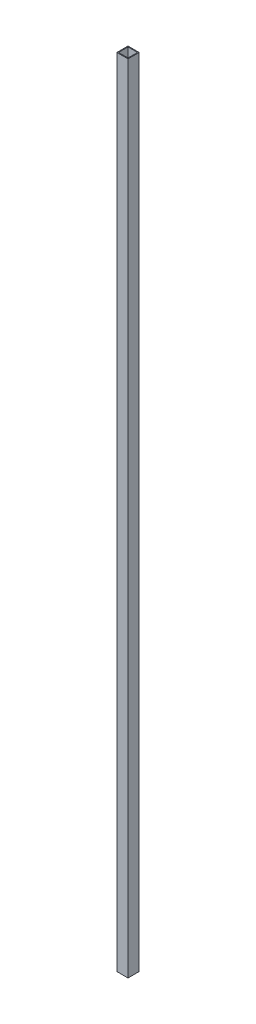
SolidWorks part; units mm, degrees
ref_plane "Front Plane" through (0, 0, 0) normal (0, 0, 1) x (1, 0, 0)
ref_plane "Top Plane" through (0, 0, 0) normal (0, 1, 0) x (1, 0, 0)
ref_plane "Right Plane" through (0, 0, 0) normal (1, 0, 0) x (0, 0, -1)
sketch "Sketch1" plane through (0, 0, 0) normal (0, 1, 0) x (1, 0, 0)
  line L0 (-1, -1) -> (-13, -1)
  line L1 (0, 0) -> (-14, 0)
  line L2 (0, 0) -> (0, -14)
  line L3 (0, -14) -> (-14, -14)
  line L4 (-14, 0) -> (-14, -14)
  line L5 (-13, -1) -> (-13, -13)
  line L6 (-1, -13) -> (-13, -13)
  line L7 (-1, -1) -> (-1, -13)
  dimension "D1" = 14
  dimension "D2" = 14
  dimension "D3" = 1
extrude "Boss-Extrude1" add sketch "Sketch1" along normal blind 1000 contours L4 L3 L2 L1 | L5 L6 L7 L0
